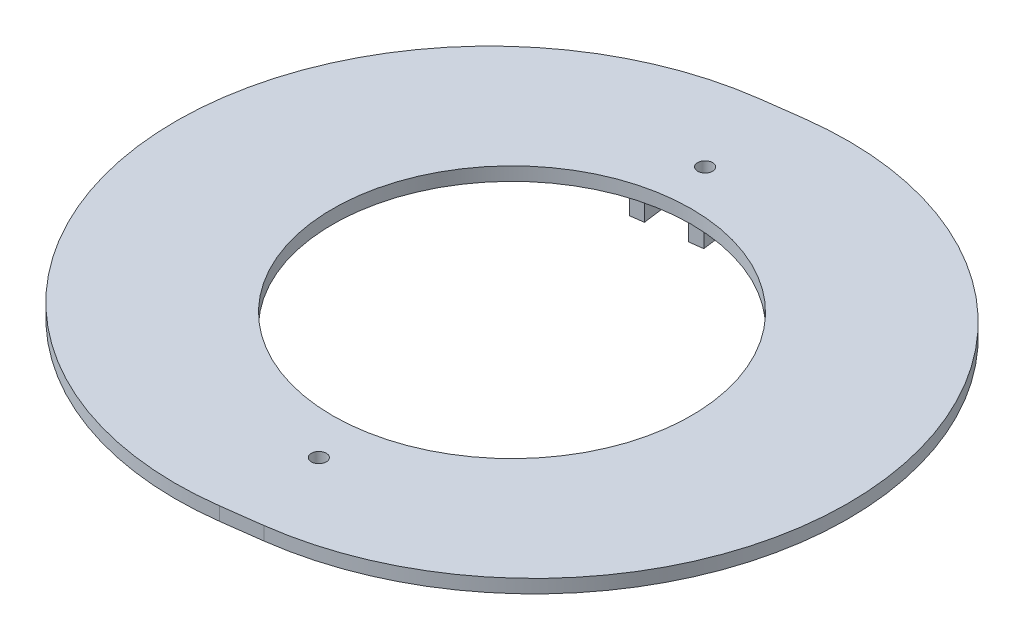
SolidWorks part; units mm, degrees
ref_plane "Front Plane" through (0, 0, 0) normal (0, 0, 1) x (1, 0, 0)
ref_plane "Top Plane" through (0, 0, 0) normal (0, 1, 0) x (1, 0, 0)
ref_plane "Right Plane" through (0, 0, 0) normal (1, 0, 0) x (0, 0, -1)
sketch "Sketch1" plane through (0, 0, 0) normal (0, 1, 0) x (1, 0, 0)
  circle A0 centre (0, 0) radius 0.5
  dimension "D1" = 1
sketch "Sketch2" plane through (0, 0, 0) normal (0, 1, 0) x (1, 0, 0)
  line L0 (0, 0) -> (0, -3.6) construction
  line L1 (0, 0) -> (0, -1.12) construction
  line L2 (-1, -1.12) -> (1, -1.12) construction
  line L3 (0, -3.6) -> (-2.2, -3.6) construction
  line L4 (0, -3.6) -> (2.2, -3.6) construction
  circle A0 centre (-2.2, -3.6) radius 0.65
  circle A1 centre (-1, -1.12) radius 0.375
  circle A2 centre (1, -1.12) radius 0.375
  circle A3 centre (2.2, -3.6) radius 0.65
  point P8 (0, -1.12)
  dimension "D1" = 3.6
  dimension "D5" = 0.75
  dimension "D6" = 1.3
  dimension "D2" = 1.12
  dimension "D3" = 2
  dimension "D4" = 2.2
sketch "Sketch3" plane through (0, 0, 0) normal (0, 1, 0) x (1, 0, 0)
  line L0 (-1.6416, -3.5265) -> (-2.7584, -3.6735)
  line L1 (-0.5, -3.6) -> (0.2484, -3.6) construction
  line L4 (-0.5333, -1.12) -> (-1.4667, -1.12) construction
  line L5 (-1.9887, -2.4018) -> (-2.4113, -4.7982)
  circle A0 centre (-2.2, -3.6) radius 0.1884
  point P11 (-1, -1.12)
  point P14 (-1, -1.12)
  point P16 (1, -1.12)
  point P18 (-2.2, -3.6)
  dimension "D1" = 3.6
  dimension "D2" = 2.2
  dimension "D3" = 7.5
  dimension "D5" = 0.9335
  dimension "D4" = 180
  dimension "D6" = 80
ref_plane "Shuttle-Center-Plane" through (0.4284, 0, 3.254) normal (-0.1305, 0, -0.9914) x (-0.9914, 0, 0.1305)
sketch "Sketch6" plane through (0.4284, 0, 3.254) normal (-0.1305, 0, -0.9914) x (-0.9914, 0, 0.1305)
  line L0 (2.6511, 0) -> (2.6511, 3.1485)
  line L1 (2.6511, 0) -> (2.6511, -2)
  dimension "D1" = 2
sketch "ShuttleBaseLayout" plane through (0.1377, 0, 3.2922) normal (0.1305, 0, 0.9914) x (0.9914, 0, -0.1305)
  line L0 (-2.3579, -0.3457) -> (-2.3579, 2.5883) construction
  line L8 (-2.3579, 0) -> (-4.8788, 0) construction
  line L9 (-4.8788, 0) -> (-6.7695, 0)
  line L10 (-6.7695, 0) -> (-11.4963, 0)
  line L11 (-11.4963, 0) -> (-20.6277, 11.9003)
  line L12 (-20.6277, 11.9003) -> (-17.6527, 14.1832)
  line L13 (-17.6527, 14.1832) -> (-6.7695, 0) construction
  line L14 (-17.6527, 14.1832) -> (-16.4626, 15.0963)
  line L15 (-16.4626, 15.0963) -> (-4.8788, 0)
  line L16 (-14.2052, 15.4397) -> (9.0211, -14.8294) construction
  dimension "D5" = 37.5
  dimension "D6" = 1.5
  dimension "D7" = 15
  dimension "D8" = 3.5
  dimension "D9" = 5.25
sketch "Sketch88" plane through (0.4284, 0, 3.254) normal (-0.1305, 0, -0.9914) x (-0.9914, 0, 0.1305)
  line L0 (36.4179, 32.0963) -> (7.9529, -5) construction
  line L1 (7.9529, -5) -> (9.2133, -5)
  line L2 (9.2133, -5) -> (37.6783, 32.0963)
  line L4 (11.7895, 0) -> (20.9209, 11.9003) construction
  line L5 (7.0627, 0) -> (11.7895, 0) construction
  line L6 (7.9529, -5) -> (20.9209, 11.9003)
  line L7 (20.9209, 11.9003) -> (21.236, 11.9003) construction
  line L8 (21.236, 11.9003) -> (36.733, 32.0963) construction
  line L9 (36.733, 32.0963) -> (37.6783, 32.0963)
  line L10 (36.733, 32.0963) -> (36.4179, 32.0963)
  line L11 (20.9209, 11.9003) -> (36.4179, 32.0963)
  dimension "D1" = 1
  dimension "D2" = 5
  dimension "D3" = 17
  dimension "D4" = 0.25
ref_plane "TopPlane" through (0, 32.0963, 0) normal (0, 1, 0) x (1, 0, 0)
sketch "Sketch89" plane through (0, 32.0963, 0) normal (0, 1, 0) x (1, 0, 0)
  line L0 (-2.2, -3.6) -> (-36.9276, -8.172) construction
  line L1 (-6.772, 31.1276) -> (2.372, -38.3276) construction
  line L2 (-6.772, 31.1276) -> (-2.4096, 31.7019)
  line L3 (2.372, -38.3276) -> (6.7343, -37.7533)
  line L4 (-2.4096, 31.7019) -> (6.7343, -37.7533) construction
  line L5 (2.1624, -3.0257) -> (-2.2, -3.6) construction
  line L6 (3.2479, -28.126) -> (4.5532, -38.0404) construction
  line L7 (-3.2855, 21.5003) -> (-4.5908, 31.4147) construction
  arc A0 (-6.772, 31.1276) -> (2.372, -38.3276) centre (-2.2, -3.6) ccw
  arc A1 (-2.4096, 31.7019) -> (6.7343, -37.7533) centre (2.1624, -3.0257) cw
  circle A2 centre (-0.0188, -3.3128) radius 20
  circle A3 centre (3.2479, -28.126) radius 0.836
  circle A4 centre (-3.2855, 21.5003) radius 0.836
  point P0 (-2.2, -3.6)
  point P7 (-36.9276, -8.172)
  dimension "D2" = 40
  dimension "D3" = 1.672
  dimension "D1" = 4.4
  dimension "D4" = 10
extrude "Boss-Extrude1" add sketch "Sketch89" along normal blind 1.5
sketch "Sketch90" plane through (0, 32.0963, 0) normal (0, -1, 0) x (1, 0, 0)
  line L0 (1.0667, 28.4131) -> (0.4141, 23.4559)
  line L1 (1.0667, 28.4131) -> (-0.4205, 28.6089)
  line L2 (0.4141, 23.4559) -> (-1.0731, 23.6517)
  line L3 (-0.4205, 28.6089) -> (-1.0731, 23.6517)
  line L4 (-6.772, -31.1276) -> (2.372, 38.3276) construction
  line L5 (5.4291, 27.8388) -> (4.7764, 22.8816)
  line L6 (5.4291, 27.8388) -> (6.9162, 27.643)
  line L7 (4.7764, 22.8816) -> (6.2636, 22.6858)
  line L8 (6.9162, 27.643) -> (6.2636, 22.6858)
  line L9 (-2.4096, -31.7019) -> (6.7343, 37.7533) construction
  line L10 (-0.4517, -16.8302) -> (-1.1044, -21.7875)
  line L11 (-0.4517, -16.8302) -> (1.0354, -17.026)
  line L12 (-1.1044, -21.7875) -> (0.3828, -21.9832)
  line L13 (1.0354, -17.026) -> (0.3828, -21.9832)
  line L14 (-5.4667, -21.2131) -> (-4.8141, -16.2559)
  line L15 (-5.4667, -21.2131) -> (-6.9539, -21.0174)
  line L16 (-4.8141, -16.2559) -> (-6.3012, -16.0601)
  line L17 (-6.9539, -21.0174) -> (-6.3012, -16.0601)
  line L18 (2.372, 38.3276) -> (6.7343, 37.7533) construction
  line L19 (0.7404, 25.9345) -> (-5.1404, -18.7345) construction
  dimension "D1" = 1.5
  dimension "D2" = 5
  dimension "D3" = 15
extrude "Boss-Extrude2" add sketch "Sketch90" along normal blind 2
equation "\"DriveAngle\"= 37.5"
equation "\"ThreadedRodOffset\"=1.5"
equation "\"ShuttleOffsetCenter\"= 3.5mm"
equation "\"RotationalCenterAP\"=3.6"
equation "\"D1@Sketch3\"=\"RotationalCenterAP\""
equation "\"RotationalCenterML\"= 2.2"
equation "\"D2@Sketch3\"=\"RotationalCenterML\""
equation "\"BaseRotationAngle\"= \"RotationalSpacing\" / 2"
equation "\"D3@Sketch3\"=\"BaseRotationAngle\""
equation "\"HolderBottomDistanceAboveProjection\"= 5mm"
equation "\"HolderHeight\"=1.5"
equation "\"CannulaOffset\"= 2"
equation "\"D1@Sketch6\"=\"CannulaOffset\""
equation "\"BaseWidening\"=0.5"
equation "\"TetrodeCanulaDiameter\"= 1.3mm"
equation "\"D6@Sketch2\"=\"TetrodeCanulaDiameter\""
equation "\"StimElectrodeCanulaDiameter\"= 0.75mm"
equation "\"D5@Sketch2\"=\"StimElectrodeCanulaDiameter\""
equation "\"TapDrill0_80\"=1.19063"
equation "\"LooseTapDrill0_80\"=1.52"
equation "\"StabilizerRodHole\"=0.8128"
equation "\"RetainingSlotWidth\"=0.5"
equation "\"DriveToEIBSpace\"= 9"
equation "\"0_80_TravelDistance\"=15"
equation "\"D6@ShuttleBaseLayout\" = \"ThreadedRodOffset\""
equation "\"D7@ShuttleBaseLayout\" = \"0_80_TravelDistance\""
equation "\"D5@ShuttleBaseLayout\" = \"DriveAngle\""
equation "\"D8@ShuttleBaseLayout\" = \"ShuttleOffsetCenter\""
equation "\"StabilizerTo0_80Distance\"=2.5"
equation "\"30gaTubingSupport\"=3.5"
equation "\"23GaChannel\"=1.25"
equation "\"RotationalSpacing\"= 15"
equation "\"HalfNumberOfShuttles\"= 4"
equation "\"WeightReductionCutCenter\"= 80"
equation "\"D6@Sketch3\"=\"WeightReductionCutCenter\""
equation "\"EIB-Height\"= 15"
equation "\"19gaLength\"=7.5"
equation "\"ConeThickness\"= 1"
equation "\"D1@Sketch88\"=\"ConeThickness\""
equation "\"ConeBelowBase\"=5"
equation "\"D2@Sketch88\"=\"ConeBelowBase\""
equation "\"ConeAboveRim\"= 17"
equation "\"D3@Sketch88\"=\"ConeAboveRim\""
equation "\"ConeMountAboveBottomRim\"=3"
equation "\"ConeThicknessReduction\"= 0.25"
equation "\"D4@Sketch88\"=\"ConeThicknessReduction\""
equation "\"ConeHeightBlockReduction\"= 3"
equation "\"Rim\"=10"
equation "\"RimHeight\"=2.5"
equation "\"RimHeightLessOffset\"=2.5"
equation "\"D3@Sketch89\"=\"LooseTapDrill0_80\"*1.1"
